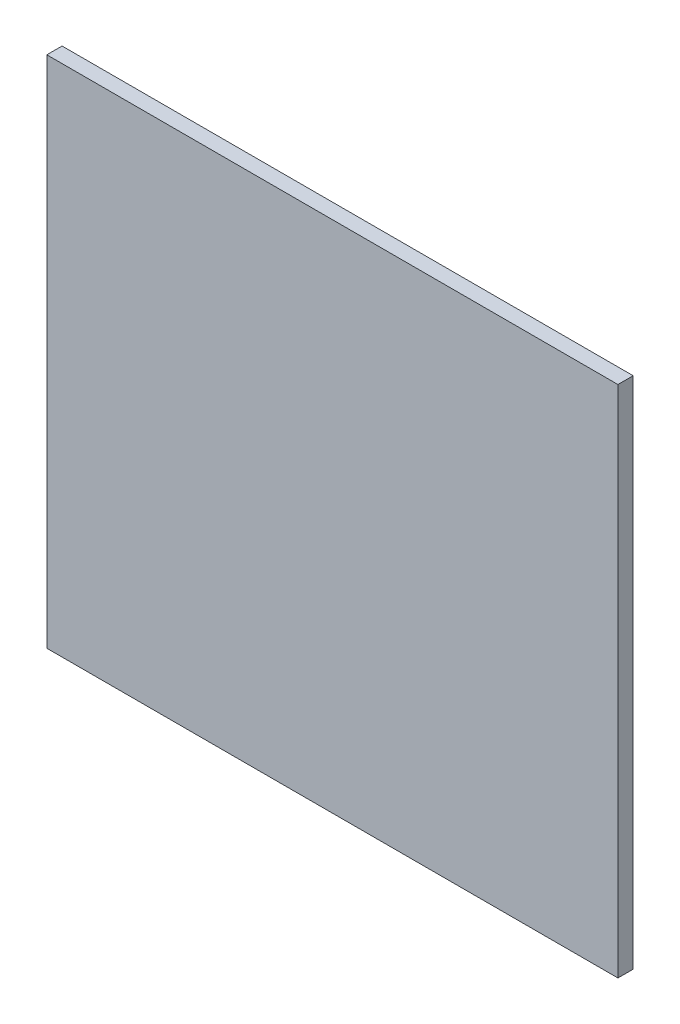
SolidWorks part; units mm, degrees
material "Береза"
ref_plane "Спереди" through (0, 0, 0) normal (0, 0, 1) x (1, 0, 0)
ref_plane "Сверху" through (0, 0, 0) normal (0, 1, 0) x (1, 0, 0)
ref_plane "Справа" through (0, 0, 0) normal (1, 0, 0) x (0, 0, -1)
sketch "Эскиз1" plane through (0, 0, 0) normal (0, 0, 1) x (1, 0, 0)
  line L1 (0, 0) -> (300, 0)
  line L2 (0, 0) -> (0, 270)
  line L3 (0, 270) -> (300, 270)
  line L4 (300, 0) -> (300, 270)
  dimension "D1" = 300
  dimension "D2" = 270
extrude "Бобышка-Вытянуть1" add sketch "Эскиз1" along normal blind 8
